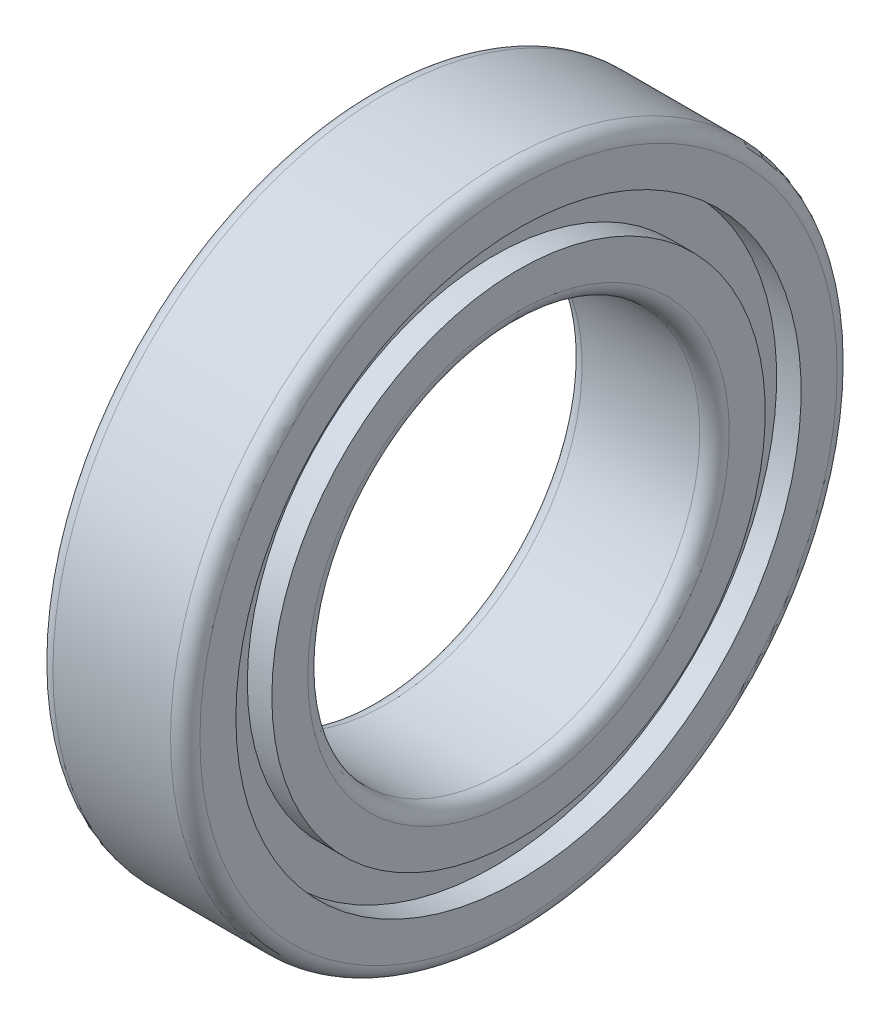
SolidWorks part; units mm, degrees
material "AISI 1020"
ref_plane "Спереди" through (0, 0, 0) normal (0, 0, 1) x (1, 0, 0)
ref_plane "Сверху" through (0, 0, 0) normal (0, 1, 0) x (1, 0, 0)
ref_plane "Справа" through (0, 0, 0) normal (1, 0, 0) x (0, 0, -1)
sketch "Эскиз1" plane through (0, 0, 0) normal (0, 0, 1) x (1, 0, 0)
  line L0 (-1000, 0) -> (49000, 0) construction
  line L1 (0, -1000) -> (0, 49000) construction
  line L2 (6, 20) -> (-6, 20)
  line L3 (-7.5, 21.5) -> (-7.5, 25.1667)
  line L4 (-7.5, 25.1667) -> (-5, 25.1667)
  line L5 (-5, 25.1667) -> (-5, 28.8333)
  line L6 (-5, 28.8333) -> (-7.5, 28.8333)
  line L7 (-7.5, 28.8333) -> (-7.5, 32.5)
  line L8 (-6, 34) -> (6, 34)
  line L9 (7.5, 28.8333) -> (7.5, 32.5)
  line L10 (5, 28.8333) -> (7.5, 28.8333)
  line L11 (5, 25.1667) -> (5, 28.8333)
  line L12 (7.5, 25.1667) -> (5, 25.1667)
  line L13 (7.5, 21.5) -> (7.5, 25.1667)
  arc A0 (-6, 20) -> (-7.5, 21.5) centre (-6, 21.5) cw
  arc A1 (-7.5, 32.5) -> (-6, 34) centre (-6, 32.5) cw
  arc A2 (7.5, 32.5) -> (6, 34) centre (6, 32.5) ccw
  arc A3 (6, 20) -> (7.5, 21.5) centre (6, 21.5) ccw
  point P23 (0, 34)
  point P27 (0, 20)
  dimension "_r" = 1.5
  dimension "_d" = 40
  dimension "D" = 68
  dimension "B" = 15
  dimension "D2" = 10
revolve "Повернуть1" add sketch "Эскиз1" angle 360 about L0
equation "\"D2@Эскиз1\"= \"B@Эскиз1\" / 3 * 2"
